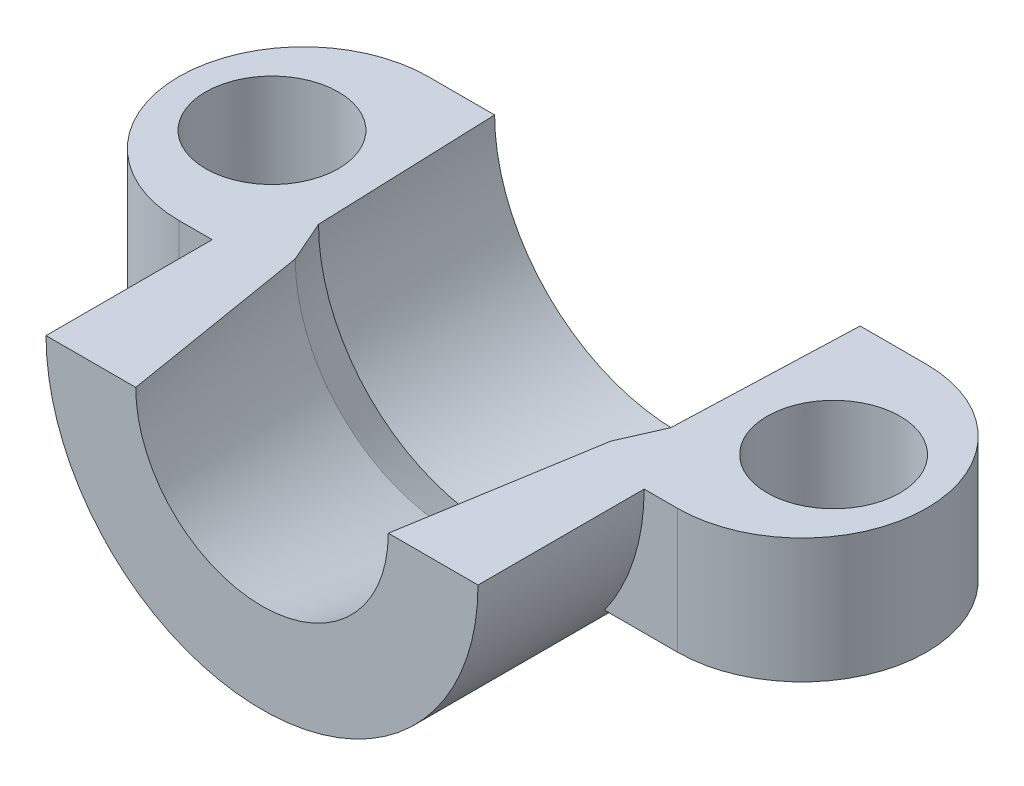
SolidWorks part; units mm, degrees
material "Thornel Mat VMA"
ref_plane "Front Plane" through (0, 0, 0) normal (0, 0, 1) x (1, 0, 0)
ref_plane "Top Plane" through (0, 0, 0) normal (0, 1, 0) x (1, 0, 0)
ref_plane "Right Plane" through (0, 0, 0) normal (1, 0, 0) x (0, 0, -1)
sketch "Sketch1" plane through (0, 0, 0) normal (0, 0, 1) x (1, 0, 0)
  circle A0 centre (0, 0) radius 13
  dimension "D1" = 26
extrude "Boss-Extrude1" add sketch "Sketch1" against normal blind 25
sketch "Sketch2" plane through (0, 0, 0) normal (1, 0, 0) x (0, 0, -1)
  line L0 (0, 0) -> (0, 7.6)
  line L1 (0, 13) -> (0, -13) construction
  line L2 (0, 7.6) -> (11.5, 9.5)
  line L3 (11.5, 9.5) -> (14, 10.6)
  line L5 (25, -13) -> (25, 13) construction
  line L6 (25, 11) -> (25, 0)
  line L7 (25, 0) -> (0, 0)
  line L8 (14, 10.6) -> (25, 11)
  dimension "D1" = 7.6
  dimension "D2" = 9.5
  dimension "D3" = 10.6
  dimension "D4" = 11
  dimension "D5" = 11
  dimension "D6" = 13.5
revolve "Cut-Revolve1" cut sketch "Sketch2" angle 360 about L7
sketch "Sketch3" plane through (0, 0, 0) normal (0, 1, 0) x (1, 0, 0)
  line L0 (-13, 25) -> (-13, 10)
  line L1 (-13, 25) -> (-13, 0) construction
  line L2 (-13, 10) -> (-15, 10)
  line L3 (-13, 25) -> (-15, 25)
  line L4 (0, 0) -> (0, 26.1438) construction
  line L8 (13, 25) -> (15, 25)
  line L9 (13, 10) -> (15, 10)
  line L10 (13, 25) -> (13, 10)
  arc A0 (-15, 10) -> (-15, 25) centre (-15, 17.5) cw
  arc A2 (15, 10) -> (15, 25) centre (15, 17.5) ccw
  dimension "D1" = 15
  dimension "D2" = 2
extrude "Boss-Extrude2" add sketch "Sketch3" along normal mid plane 15
sketch "Sketch4" plane through (0, 0, -25) normal (0, 0, -1) x (-1, 0, 0)
  line L11 (-13, 7.5) -> (-13, -7.5)
  line L12 (-13, -7.5) -> (-8.0467, -7.5)
  line L14 (13, 7.5) -> (13, -7.5)
  line L20 (-8.0467, 7.5) -> (-13, 7.5)
  line L21 (13, -7.5) -> (8.0467, -7.5)
  line L23 (8.0467, 7.5) -> (13, 7.5)
  arc A6 (-8.0467, 7.5) -> (-8.0467, -7.5) centre (0, 0) ccw
  circle A7 centre (0, 0) radius 11 construction
  arc A9 (8.0467, -7.5) -> (8.0467, 7.5) centre (0, 0) ccw
extrude "Boss-Extrude3" add sketch "Sketch4" against normal blind 15
sketch "Sketch5" plane through (0, 7.5, 0) normal (0, 1, 0) x (1, 0, 0)
  circle A2 centre (16.9, 17.5) radius 3
  arc A4 (-15, 25) -> (-15, 10) centre (-15, 17.5) ccw construction
  arc A7 (15, 10) -> (15, 25) centre (15, 17.5) ccw construction
  circle A8 centre (-16.9, 17.5) radius 3
  point P10 (22.5, 17.5)
  point P11 (-22.5, 17.5)
  dimension "D1" = 6
  dimension "D2" = 5.6
  dimension "D3" = 5.6
extrude "Cut-Extrude1" cut sketch "Sketch5" against normal through all
sketch "Sketch6" plane through (0, 7.5, 0) normal (0, 1, 0) x (1, 0, 0)
  circle A0 centre (-16.9, 17.5) radius 4.45
  circle A1 centre (16.9, 17.5) radius 4.45
  circle A2 centre (-16.9, 17.5) radius 3 construction
  circle A3 centre (16.9, 17.5) radius 3 construction
  dimension "D1" = 8.9
extrude "Cut-Extrude2" cut sketch "Sketch6" against normal blind 3
sketch "Sketch7" plane through (0, -7.5, 0) normal (0, -1, 0) x (1, 0, 0)
  circle A0 centre (-16.9, -17.5) radius 4
  circle A1 centre (16.9, -17.5) radius 4
  circle A2 centre (-16.9, -17.5) radius 3 construction
  dimension "D1" = 8
extrude "Cut-Extrude3" cut sketch "Sketch7" against normal blind 7.5
sketch "Sketch8" plane through (0, 0, 0) normal (0, 1, 0) x (1, 0, 0)
  line L0 (0, 0) -> (0, 55.5084) construction
  line L1 (-25, 39.0176) -> (25, 39.0176)
  line L2 (-25, 39.0176) -> (-25, -10.9824)
  line L3 (-25, -10.9824) -> (25, -10.9824)
  line L4 (25, 39.0176) -> (25, -10.9824)
  dimension "D1" = 50
  dimension "D2" = 50
  dimension "D3" = 25
extrude "Cut-Extrude4" cut sketch "Sketch8" along normal through all
equation "\"D3@Sketch5\"=\"D2@Sketch5\""
